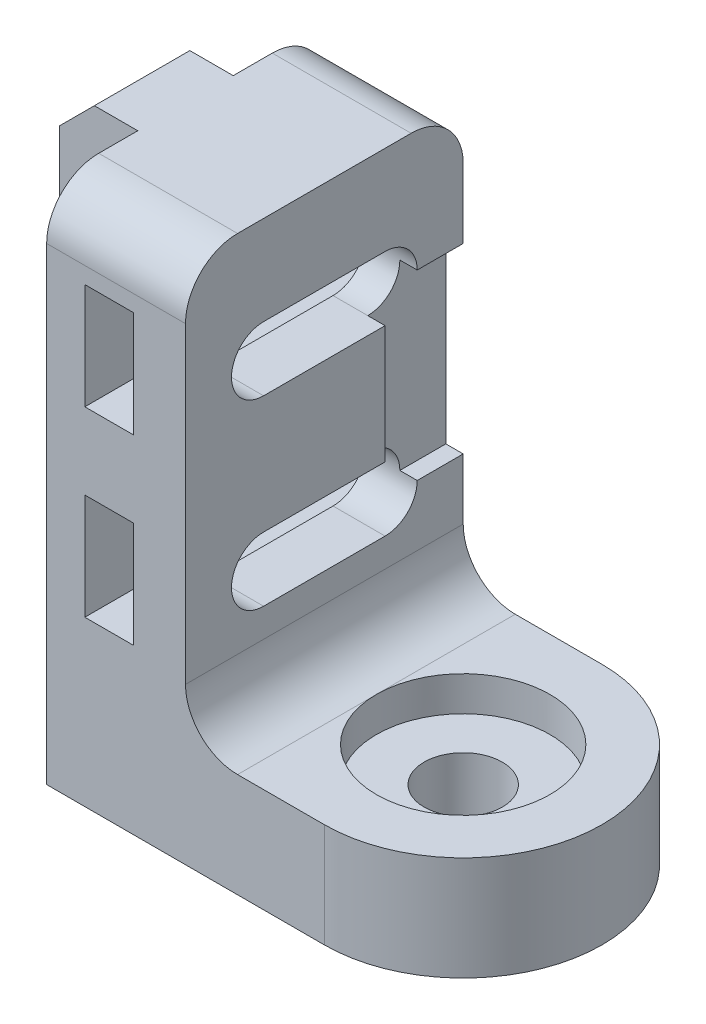
SolidWorks part; units mm, degrees
ref_plane "Front Plane" through (0, 0, 0) normal (0, 0, 1) x (1, 0, 0)
ref_plane "Top Plane" through (0, 0, 0) normal (0, 1, 0) x (1, 0, 0)
ref_plane "Right Plane" through (0, 0, 0) normal (1, 0, 0) x (0, 0, -1)
sketch "Sketch1" plane through (0, 0, 0) normal (1, 0, 0) x (0, 0, -1)
  line L0 (-32.8466, 27.9115) -> (-32.8466, -2.0885)
  line L5 (-32.8466, -2.0885) -> (-48.8466, -2.0885)
  line L6 (-48.8466, -2.0885) -> (-48.8466, 27.9115)
  line L8 (-48.8466, 27.9115) -> (-32.8466, 27.9115)
  dimension "D9" = 16
  dimension "D10" = 30
extrude "Boss-Extrude1" add sketch "Sketch1" along normal blind 8
sketch "Sketch2" plane through (0, 0, 0) normal (-1, 0, 0) x (0, 0, 1)
  line L0 (40.8466, 5.9115) -> (40.8466, 12.9115) construction
  line L1 (48.8466, 27.9115) -> (48.8466, -2.0885) construction
  line L3 (38.0966, 27.9115) -> (43.5966, 27.9115)
  line L4 (38.0966, 27.9115) -> (38.0966, -2.0885)
  line L5 (38.0966, -2.0885) -> (43.5966, -2.0885)
  line L6 (43.5966, 27.9115) -> (43.5966, -2.0885)
  line L7 (38.0966, 27.9115) -> (43.5966, -2.0885) construction
  line L8 (38.0966, -2.0885) -> (43.5966, 27.9115) construction
  line L9 (48.8466, -2.0885) -> (32.8466, -2.0885) construction
  line L10 (32.8466, 27.9115) -> (48.8466, 27.9115) construction
  point P5 (40.8466, 12.9115)
  dimension "D1" = 5.5
  dimension "D3" = 8
extrude "Boss-Extrude2" add sketch "Sketch2" along normal blind 4.5
chamfer "Chamfer1" distance 2 angle 45 2 edges at (-4.5, -2.0885, 40.8466) (-4.5, 27.9115, 40.8466)
sketch "Sketch6" plane through (0, -2.0885, 0) normal (0, -1, 0) x (1, 0, 0)
  line L0 (8, 48.8466) -> (16, 48.8466)
  line L2 (16, 32.8466) -> (8, 32.8466)
  line L3 (8, 32.8466) -> (8, 48.8466)
  arc A0 (16, 32.8466) -> (16, 48.8466) centre (16, 40.8466) ccw
  circle A1 centre (16, 40.8466) radius 2.25
  dimension "D2" = 4.5
  dimension "D1" = 8
extrude "Boss-Extrude3" add sketch "Sketch6" against normal blind 6 contours A0 L0 L3 L2
fillet "Fillet6" radius 3 1 edges at (8, 3.9115, 40.8466)
sketch "Sketch7" plane through (8, 0, 0) normal (1, 0, 0) x (0, 0, -1)
  line L0 (-32.8466, 6.9115) -> (-32.8466, 27.9115) construction
  line L1 (-48.8466, 23.9615) -> (-32.8466, 23.9615)
  line L2 (-48.8466, 23.9615) -> (-48.8466, 17.8615)
  line L3 (-48.8466, 17.8615) -> (-32.8466, 17.8615)
  line L4 (-32.8466, 23.9615) -> (-32.8466, 17.8615)
  line L5 (-48.8466, 27.9115) -> (-48.8466, 6.9115) construction
  line L7 (-48.8466, 13.4615) -> (-32.8466, 13.4615)
  line L8 (-48.8466, 13.4615) -> (-48.8466, 7.3615)
  line L9 (-48.8466, 7.3615) -> (-32.8466, 7.3615)
  line L10 (-32.8466, 13.4615) -> (-32.8466, 7.3615)
  point P6 (-48.8466, 20.9115)
  dimension "D1" = 10.5
  dimension "D2" = 6.1
  dimension "D3" = 7
extrude "Cut-Extrude1" cut sketch "Sketch7" against normal blind 2.8 from offset 3 offset against normal yes
sketch "Sketch8" plane through (8, 0, 0) normal (1, 0, 0) x (0, 0, -1)
  line L0 (-44.3466, 20.9115) -> (-37.3466, 20.9115) construction
  line L1 (-44.3466, 22.7615) -> (-37.3466, 22.7615)
  line L2 (-44.3466, 19.0615) -> (-37.3466, 19.0615)
  line L3 (-44.3466, 10.4115) -> (-37.3466, 10.4115) construction
  line L4 (-44.3466, 12.2615) -> (-37.3466, 12.2615)
  line L5 (-44.3466, 8.5615) -> (-37.3466, 8.5615)
  line L6 (-32.8466, 27.9115) -> (-48.8466, 27.9115) construction
  arc A0 (-44.3466, 22.7615) -> (-44.3466, 19.0615) centre (-44.3466, 20.9115) ccw
  arc A1 (-37.3466, 19.0615) -> (-37.3466, 22.7615) centre (-37.3466, 20.9115) ccw
  arc A2 (-44.3466, 12.2615) -> (-44.3466, 8.5615) centre (-44.3466, 10.4115) ccw
  arc A3 (-37.3466, 8.5615) -> (-37.3466, 12.2615) centre (-37.3466, 10.4115) ccw
  point P2 (-40.8466, 20.9115)
  point P7 (-40.8466, 10.4115)
  point P19 (-40.8466, 27.9115)
  dimension "D4" = 1.85
  dimension "D1" = 10.5
  dimension "D2" = 7
  dimension "D3" = 7
extrude "Cut-Extrude2" cut sketch "Sketch8" against normal blind 5
sketch "Sketch9" plane through (8, 0, 0) normal (1, 0, 0) x (0, 0, -1)
  line L0 (-32.8466, 6.9115) -> (-32.8466, 27.9115) construction
  line L1 (-32.8466, 20.9115) -> (-37.3466, 20.9115)
  line L2 (-32.8466, 20.9115) -> (-32.8466, 10.4115)
  line L3 (-32.8466, 10.4115) -> (-37.3466, 10.4115)
  line L4 (-37.3466, 20.9115) -> (-37.3466, 10.4115)
extrude "Cut-Extrude3" cut sketch "Sketch9" against normal blind 1
sketch "Sketch10" plane through (0, 3.9115, 0) normal (0, 1, 0) x (1, 0, 0)
  circle A0 centre (16, -40.8466) radius 5
extrude "Cut-Extrude4" cut sketch "Sketch10" against normal blind 2
fillet "Fillet7" radius 3 2 edges at (4, 27.9115, 32.8466) (4, 27.9115, 48.8466)
